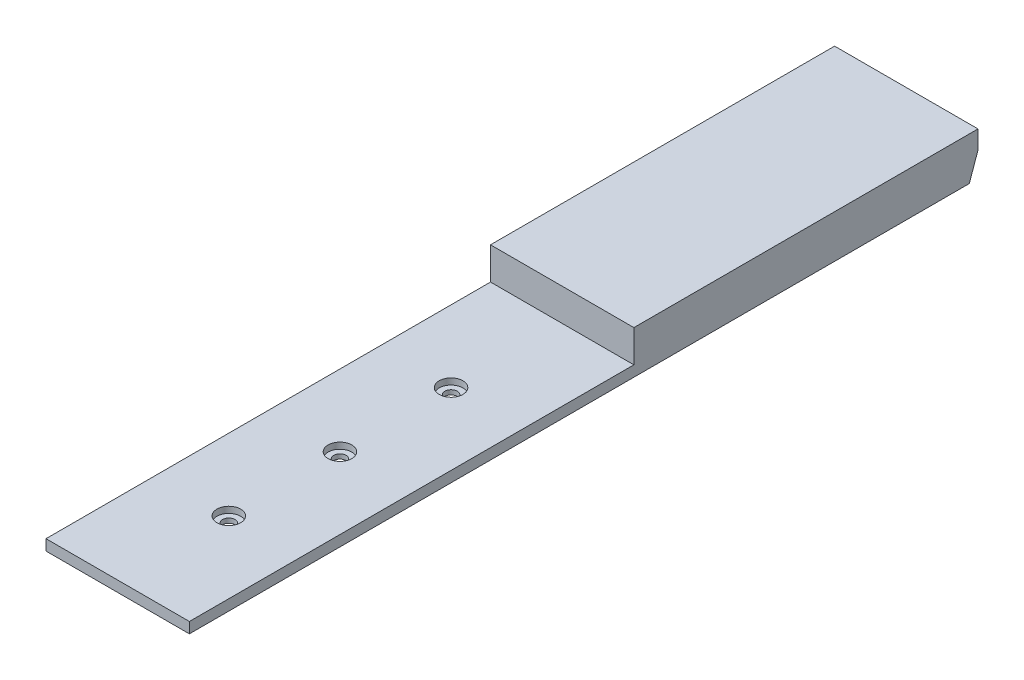
SolidWorks part; units mm, degrees
ref_plane "Front Plane" through (0, 0, 0) normal (0, 0, 1) x (1, 0, 0)
ref_plane "Top Plane" through (0, 0, 0) normal (0, 1, 0) x (1, 0, 0)
ref_plane "Right Plane" through (0, 0, 0) normal (1, 0, 0) x (0, 0, -1)
sketch "Sketch1" plane through (0, 0, 0) normal (0, 0, 1) x (1, 0, 0)
  line L1 (-31.75, 0) -> (31.75, 0)
  line L2 (-31.75, 0) -> (-31.75, 19.05)
  line L3 (-31.75, 19.05) -> (31.75, 19.05)
  line L4 (31.75, 0) -> (31.75, 19.05)
  point P4 (0, 0)
  dimension "D1" = 19.05
  dimension "D2" = 63.5
extrude "Boss-Extrude1" add sketch "Sketch1" along normal blind 349.25
sketch "Sketch3" plane through (31.75, 0, 0) normal (1, 0, 0) x (0, 0, -1)
  line L0 (-349.25, 0) -> (0, 0) construction
  line L1 (-349.25, 19.05) -> (-152.4, 19.05)
  line L2 (-349.25, 19.05) -> (-349.25, 4.7625)
  line L3 (-349.25, 4.7625) -> (-152.4, 4.7625)
  line L4 (-152.4, 19.05) -> (-152.4, 4.7625)
  line L5 (0, 0) -> (0, 19.05) construction
  dimension "D1" = 4.7625
  dimension "D2" = 152.4
extrude "Cut-Extrude1" cut sketch "Sketch3" against normal through all
sketch "Sketch14" plane through (31.75, 0, 0) normal (1, 0, 0) x (0, 0, -1)
  line L0 (0, 0) -> (-25.4, 91.44) construction
  line L1 (-1.8355, 5.7338) -> (-3.9993, -0.3846) construction
  line L3 (-349.25, 0) -> (0, 0) construction
  line L4 (0, 0) -> (0, 19.05) construction
  line L5 (-3.8633, 0) -> (0, 0)
  line L6 (0, 0) -> (0, 10.9241)
  line L7 (-3.8633, 0) -> (0, 10.9241)
  point P13 (-1.6995, 6.1183)
  dimension "D1" = 91.44
  dimension "D2" = 25.4
  dimension "D3" = 35
  dimension "D4" = 6.35
extrude "Cut-Extrude2" cut sketch "Sketch14" against normal through all
hole_wizard "CBORE for M5 SBHCS1" positions "Sketch11" profile "Sketch13" counterbore size "M5" standard "ANSI Metric" end condition through all
sketch "Sketch11" plane through (0, 4.7625, 0) normal (0, 1, 0) x (1, 0, 0)
  line L0 (31.75, -349.25) -> (31.75, -152.4) construction
  line L1 (0, -349.25) -> (0, -300.0375) construction
  line L2 (-31.75, -349.25) -> (31.75, -349.25) construction
  line L3 (0, -300.0375) -> (0, -250.825) construction
  line L4 (0, -250.825) -> (0, -201.6125) construction
  line L5 (0, -201.6125) -> (0, -152.4) construction
  line L6 (-31.75, -152.4) -> (31.75, -152.4) construction
  point P0 (0, -201.6125)
  point P2 (0, -250.825)
  point P4 (0, -300.0375)
  point P13 (31.75, -250.825)
sketch "Sketch13" plane through (0, 4.7625, 201.6125) normal (1, 0, 0) x (0, 0, 1)
  line L0 (0, 0) -> (0, 4.7625)
  line L1 (0, 4.7625) -> (2.75, 4.7625)
  line L3 (2.75, 4.7625) -> (2.75, 2.75)
  line L4 (2.75, 2.75) -> (5.25, 2.75)
  line L5 (5.25, 2.75) -> (5.25, 0)
  line L7 (5.25, 0) -> (0, 0)
  line L11 (0, -6.35) -> (0, 107.95) construction
  dimension "Thru Hole Dia." = 5.5
  dimension "Thru Hole Depth" = 4.7625
  dimension "C'Bore Dia." = 10.5
  dimension "C'Bore Depth" = 2.75
